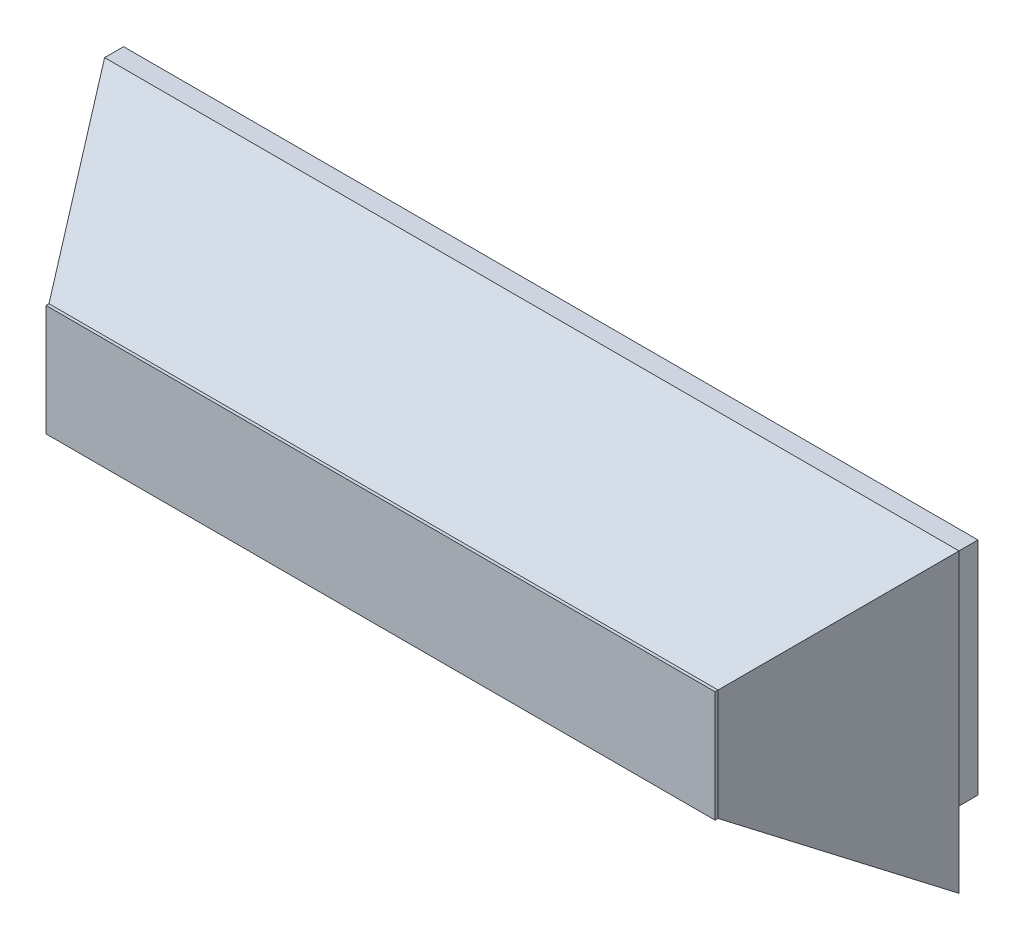
SolidWorks part; units mm, degrees
material "ABS"
ref_plane "Front Plane" through (0, 0, 0) normal (0, 0, 1) x (1, 0, 0)
ref_plane "Top Plane" through (0, 0, 0) normal (0, 1, 0) x (1, 0, 0)
ref_plane "Right Plane" through (0, 0, 0) normal (1, 0, 0) x (0, 0, -1)
sketch "Sketch1" plane through (0, 0, 0) normal (0, 0, 1) x (1, 0, 0)
  line L1 (-121.5127, 42.3818) -> (166.5873, 42.3818)
  line L2 (-121.5127, 42.3818) -> (-121.5127, -57.6182)
  line L3 (-121.5127, -57.6182) -> (166.5873, -57.6182)
  line L4 (166.5873, 42.3818) -> (166.5873, -57.6182)
  point P0 (0, 0)
  point P6 (0, 0)
  dimension "D1" = 288.1
  dimension "D2" = 100
extrude "Boss-Extrude1" add sketch "Sketch1" along normal blind 50 draft 32
sketch "Sketch2" plane through (0, 0, 50) normal (0, 0, 1) x (1, 0, 0)
  line L0 (-90.2692, -26.3748) -> (-90.2692, 11.1383)
  line L1 (-90.2692, 11.1383) -> (135.3438, 11.1383)
  line L2 (135.3438, 11.1383) -> (135.3438, -26.3748)
  line L3 (135.3438, -26.3748) -> (-90.2692, -26.3748)
extrude "Cut-Extrude1" cut sketch "Sketch2" against normal blind 50 draft 26.5
sketch "Sketch3" plane through (0, 0, 0) normal (0, 0, -1) x (-1, 0, 0)
  line L0 (-166.5873, 42.3818) -> (117.996, 42.3818)
  line L2 (117.996, 42.3818) -> (121.5127, 42.3818)
  line L3 (111.596, 32.4651) -> (-160.1873, 32.4651)
  line L4 (121.5127, 42.3818) -> (121.5127, -32.1182)
  line L5 (-166.5873, 32.4651) -> (-166.5873, 42.3818)
  line L6 (-166.5873, 32.4651) -> (-166.5873, -7.6182)
  line L8 (121.5127, 42.3818) -> (121.5127, -57.6182) construction
  line L9 (-160.1873, -7.6182) -> (-160.1873, 32.4651)
  line L11 (121.5127, -32.1182) -> (115.1127, -32.1182)
  line L15 (-160.1873, -32.1182) -> (-160.1873, -7.6182)
  line L16 (-166.5873, -7.6182) -> (-166.5873, -32.1182)
  line L17 (-166.5873, -32.1182) -> (-160.1873, -32.1182)
  line L21 (115.1127, -32.1182) -> (115.1127, 32.4651)
  line L22 (115.1127, 32.4651) -> (111.596, 32.4651)
  dimension "D1" = 74.5
  dimension "D2" = 6.4
  dimension "D3" = 6.4
extrude "Boss-Extrude2" add sketch "Sketch3" along normal blind 6.4
ref_plane "Plane1" through (0, 0, 50) normal (0, 0, 1) x (1, 0, 0)
sketch "Sketch5" plane through (0, 0, 50) normal (0, 0, 1) x (1, 0, 0)
  line L0 (-90.2692, -26.3748) -> (-90.2692, 11.1383)
  line L1 (-90.2692, 11.1383) -> (135.3438, 11.1383)
  line L2 (135.3438, 11.1383) -> (135.3438, -26.3748)
  line L3 (135.3438, -26.3748) -> (-90.2692, -26.3748)
extrude "Boss-Extrude3" add sketch "Sketch5" along normal blind 1 separate body
